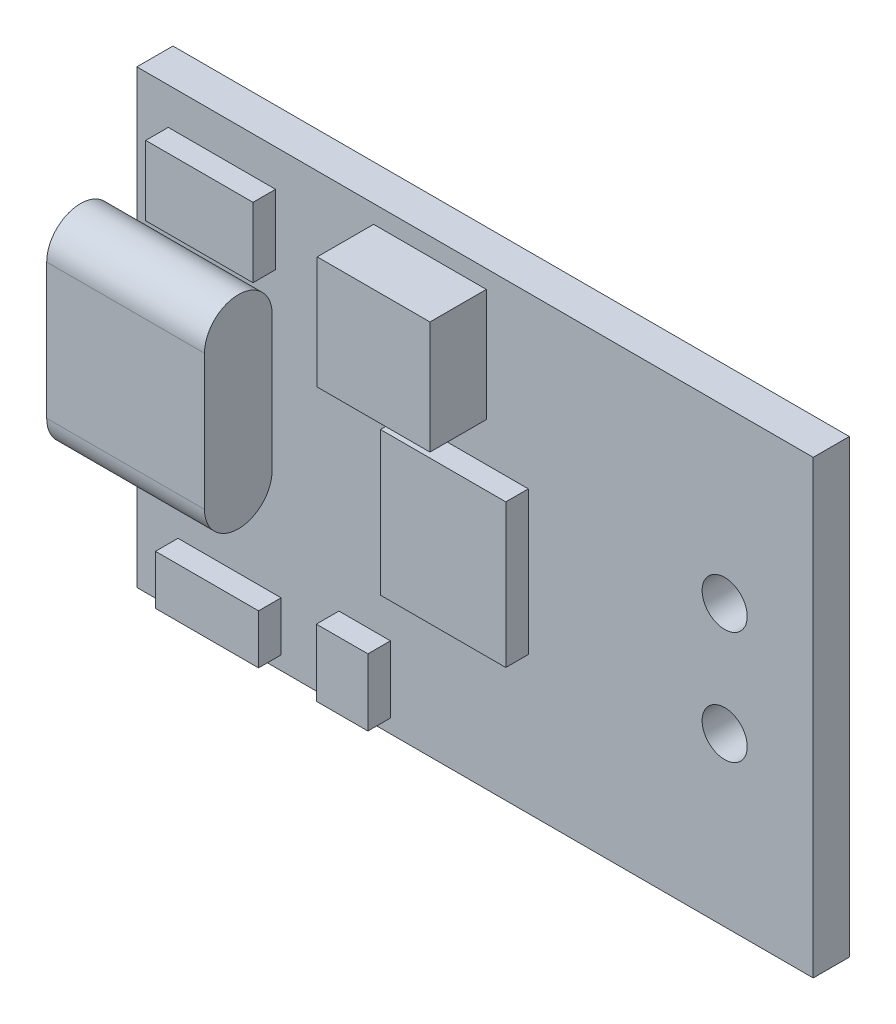
SolidWorks part; units mm, degrees
ref_plane "Front Plane" through (0, 0, 0) normal (0, 0, 1) x (1, 0, 0)
ref_plane "Top Plane" through (0, 0, 0) normal (0, 1, 0) x (1, 0, 0)
ref_plane "Right Plane" through (0, 0, 0) normal (1, 0, 0) x (0, 0, -1)
sketch "Skica1" plane through (0, 0, 0) normal (0, 0, 1) x (1, 0, 0)
  line L1 (0, 0) -> (30, 0)
  line L2 (0, 0) -> (0, 20)
  line L3 (0, 20) -> (30, 20)
  line L4 (30, 0) -> (30, 20)
  dimension "D1" = 20
  dimension "D2" = 30
extrude "Přidat vysunutím1" add sketch "Skica1" along normal blind 1.6
sketch "Skica2" plane through (0, 0, 1.6) normal (0, 0, 1) x (1, 0, 0)
  line L0 (0, 20) -> (0, 0) construction
  line L1 (10.5, 19.2) -> (15.5, 19.2)
  line L2 (10.5, 19.2) -> (10.5, 14.2)
  line L3 (10.5, 14.2) -> (15.5, 14.2)
  line L4 (15.5, 19.2) -> (15.5, 14.2)
  line L5 (30, 20) -> (0, 20) construction
  dimension "D1" = 10.5
  dimension "D2" = 5
  dimension "D3" = 5
  dimension "D4" = 0.8
extrude "Přidat vysunutím2" add sketch "Skica2" along normal blind 2.5
sketch "Skica3" plane through (0, 0, 1.6) normal (0, 0, 1) x (1, 0, 0)
  line L1 (11.8029, 12.4712) -> (17.3631, 12.4712)
  line L2 (11.8029, 12.4712) -> (11.8029, 6.1079)
  line L3 (11.8029, 6.1079) -> (17.3631, 6.1079)
  line L4 (17.3631, 12.4712) -> (17.3631, 6.1079)
  line L5 (8.961, 3.5749) -> (11.2469, 3.5749)
  line L6 (8.961, 3.5749) -> (8.961, 0.6094)
  line L7 (8.961, 0.6094) -> (11.2469, 0.6094)
  line L8 (11.2469, 3.5749) -> (11.2469, 0.6094)
  line L9 (1.8254, 2.8026) -> (6.3971, 2.8026)
  line L10 (1.8254, 2.8026) -> (1.8254, 0.6094)
  line L11 (1.8254, 0.6094) -> (6.3971, 0.6094)
  line L12 (6.3971, 2.8026) -> (6.3971, 0.6094)
  line L13 (1.3929, 18.3712) -> (6.15, 18.3712)
  line L14 (1.3929, 18.3712) -> (1.3929, 15.2822)
  line L15 (1.3929, 15.2822) -> (6.15, 15.2822)
  line L16 (6.15, 18.3712) -> (6.15, 15.2822)
extrude "Přidat vysunutím3" add sketch "Skica3" along normal blind 1
sketch "Skica4" plane through (0, 0, 1.6) normal (0, 0, 1) x (1, 0, 0)
  line L0 (26.0714, 12.4246) -> (26.0714, 7.4246) construction
  circle A0 centre (26.0714, 12.4246) radius 1
  circle A1 centre (26.0714, 7.4246) radius 1
  dimension "D1" = 2
  dimension "D2" = 2
  dimension "D3" = 5
extrude "Odebrat vysunutím1" cut sketch "Skica4" against normal blind 11
sketch "Skica5" plane through (0, 0, 0) normal (-1, 0, 0) x (0, 0, 1)
  line L0 (3.1, 13.5) -> (3.1, 7.5) construction
  line L1 (4.6, 13.5) -> (4.6, 7.5)
  line L2 (1.6, 13.5) -> (1.6, 7.5)
  line L3 (1.6, 20) -> (1.6, 0) construction
  line L5 (1.6, 20) -> (0, 20) construction
  arc A0 (4.6, 13.5) -> (1.6, 13.5) centre (3.1, 13.5) ccw
  arc A1 (1.6, 7.5) -> (4.6, 7.5) centre (3.1, 7.5) ccw
  point P2 (3.1, 10.5)
  dimension "D2" = 9
  dimension "D3" = 5
  dimension "D1" = 3
extrude "Přidat vysunutím4" add sketch "Skica5" along normal blind 1 and the other way blind 6
sketch "Skica6" plane through (-1, 0, 0) normal (-1, 0, 0) x (0, 0, 1)
  line L2 (3.1, 14.7) -> (3.1, 6.3) construction
  line L4 (1.9, 13.5) -> (1.9, 7.5)
  line L5 (4.3, 7.5) -> (4.3, 13.5)
  line L6 (1.9, 13.5) -> (1.9, 7.5)
  line L7 (4.3, 7.5) -> (4.3, 13.5)
  line L8 (2.8709, 13.0201) -> (3.3291, 13.0201)
  line L9 (2.8709, 13.0201) -> (2.8709, 7.9799)
  line L10 (2.8709, 7.9799) -> (3.3291, 7.9799)
  line L11 (3.3291, 13.0201) -> (3.3291, 7.9799)
  line L12 (2.8709, 13.0201) -> (3.3291, 7.9799) construction
  line L13 (2.8709, 7.9799) -> (3.3291, 13.0201) construction
  arc A4 (4.3, 13.5) -> (1.9, 13.5) centre (3.1, 13.5) ccw
  arc A5 (1.9, 7.5) -> (4.3, 7.5) centre (3.1, 7.5) ccw
  arc A6 (4.3, 13.5) -> (1.9, 13.5) centre (3.1, 13.5) ccw
  arc A7 (1.9, 7.5) -> (4.3, 7.5) centre (3.1, 7.5) ccw
  point P2 (3.1, 10.5)
  dimension "D1" = 0.3
extrude "Odebrat vysunutím2" cut sketch "Skica6" against normal blind 6
